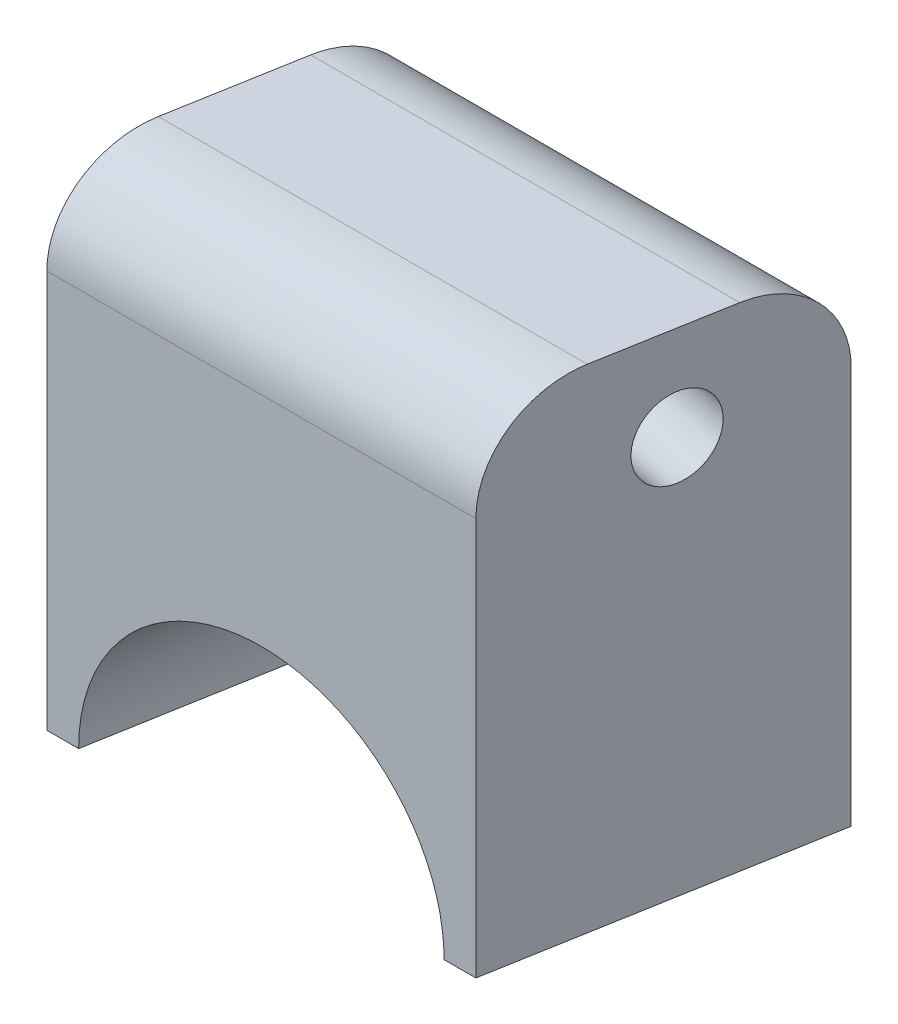
SolidWorks part; units mm, degrees
ref_plane "前视基准面" through (0, 0, 0) normal (0, 0, 1) x (1, 0, 0)
ref_plane "上视基准面" through (0, 0, 0) normal (0, 1, 0) x (1, 0, 0)
ref_plane "右视基准面" through (0, 0, 0) normal (1, 0, 0) x (0, 0, -1)
sketch "草图1" plane through (0, 0, 0) normal (0, 1, 0) x (1, 0, 0)
  line L1 (32.27, 35.1272) -> (54.915, 35.1272)
  line L5 (32.27, 35.1272) -> (29.3006, 18.287)
  line L6 (29.3006, 18.287) -> (51.9456, 18.287)
  line L7 (51.9456, 18.287) -> (54.915, 35.1272)
  line L8 (51.9456, 18.287) -> (51.2628, 14.4145)
  line L9 (29.3006, 18.287) -> (51.2628, 14.4145)
  dimension "D1" = 22.645
  dimension "D2" = 17.1
  dimension "D3" = 10
  dimension "D4" = 100
extrude "Boss-Extrude2" add sketch "草图1" along normal blind 26 contours L6 L7 L1 L5 | L6 L9 L8
sketch "Sketch2" plane through (4.0108, 0, -22.7463) normal (-0.1736, 0, 0.9848) x (0.9848, 0, 0.1736)
  line L0 (36.8304, 26) -> (36.8304, 7.7901) construction
  line L1 (25.6799, 26) -> (47.9809, 26) construction
  line L5 (27.3304, 0) -> (46.3304, 0)
  arc A1 (27.3304, 0) -> (46.3304, 0) centre (36.8304, 0) cw
  dimension "D1" = 9.5
sketch "Sketch3" plane through (0, 26, 0) normal (0, 1, 0) x (1, 0, 0)
  line L0 (29.3006, 18.287) -> (51.9456, 18.287)
  line L1 (51.9456, 18.287) -> (51.2628, 14.4145)
  line L2 (51.2628, 14.4145) -> (29.3006, 18.287)
extrude "Cut-Extrude7" cut sketch "Sketch3" against normal through all
extrude "Cut-Extrude8" cut sketch "Sketch2" against normal through all
fillet "Fillet6" radius 5 2 edges at (40.6231, 26, -18.287) (43.5925, 26, -35.1272)
sketch "Sketch7" plane through (25.2898, 0, 4.4593) normal (-0.9848, 0, -0.1736) x (-0.1736, 0, 0.9848)
  line L0 (-31.1623, 26) -> (-31.1623, 18.3688) construction
  circle A0 centre (-31.1623, 21) radius 1
  dimension "D1" = 5
  dimension "D2" = 2.988
sketch "Sketch9" plane through (47.252, 0, 8.3318) normal (0.9848, 0, 0.1736) x (0.1736, 0, -0.9848)
  line L0 (36.1965, 26) -> (36.1965, 17.5428) construction
  line L2 (32.1065, 26) -> (36.1965, 26)
  circle A0 centre (36.1965, 21) radius 1
  dimension "D1" = 5
  dimension "D2" = 4.09
hole_wizard "M5 Tapped Hole1" positions "3DSketch4" profile "Sketch11" tap size "M5" standard "GB"
sketch3d "3DSketch4"
  point P0 (53.5374, 21, -27.3148)
  point P3 (30.7011, 21, -26.2296)
sketch "Sketch11" plane through (53.5374, 21, -27.3148) normal (0, 1, 0) x (0.1736, 0, -0.9848)
  line L0 (0, 0) -> (0, 6)
  line L1 (0, 6) -> (2.1, 4.7382)
  line L2 (2.1, 4.7382) -> (2.1, 0)
  line L5 (2.1, 0) -> (0, 0)
  line L10 (0, 6) -> (-2.1, 4.7382) construction
  line L11 (0, -6.35) -> (0, 107.95) construction
  dimension "Tap Drill Dia." = 4.2
  dimension "Tap Drill Depth" = 6
  dimension "Drill Angle" = 118
cosmetic thread "Hole Thread7" parameters "D1"=4.7382, "D2"=5
cosmetic thread "Hole Thread8" parameters "D1"=4.7382, "D2"=5
